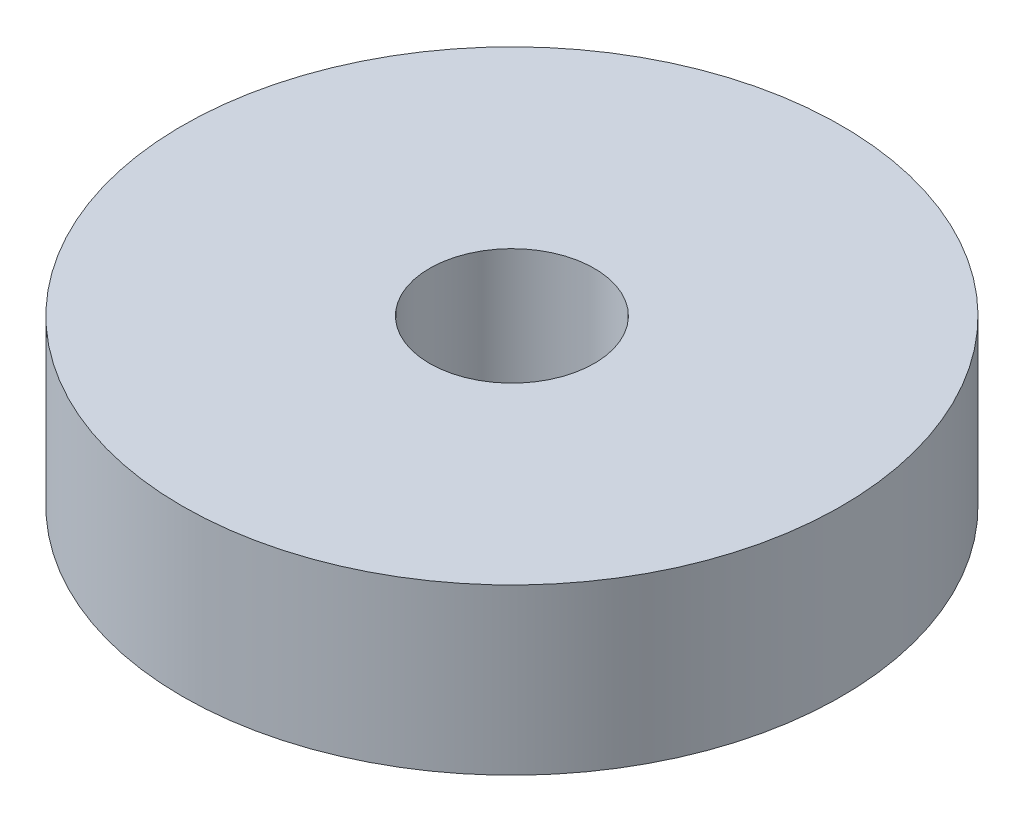
SolidWorks part; units mm, degrees
ref_plane "Front Plane" through (0, 0, 0) normal (0, 0, 1) x (1, 0, 0)
ref_plane "Top Plane" through (0, 0, 0) normal (0, 1, 0) x (1, 0, 0)
ref_plane "Right Plane" through (0, 0, 0) normal (1, 0, 0) x (0, 0, -1)
sketch "Sketch1" plane through (0, 0, 0) normal (0, 1, 0) x (1, 0, 0)
  circle A0 centre (0, 0) radius 30
  circle A1 centre (0, 0) radius 7.5
  dimension "D1" = 15
  dimension "D2" = 60
extrude "Boss-Extrude1" add sketch "Sketch1" along normal mid plane 15
